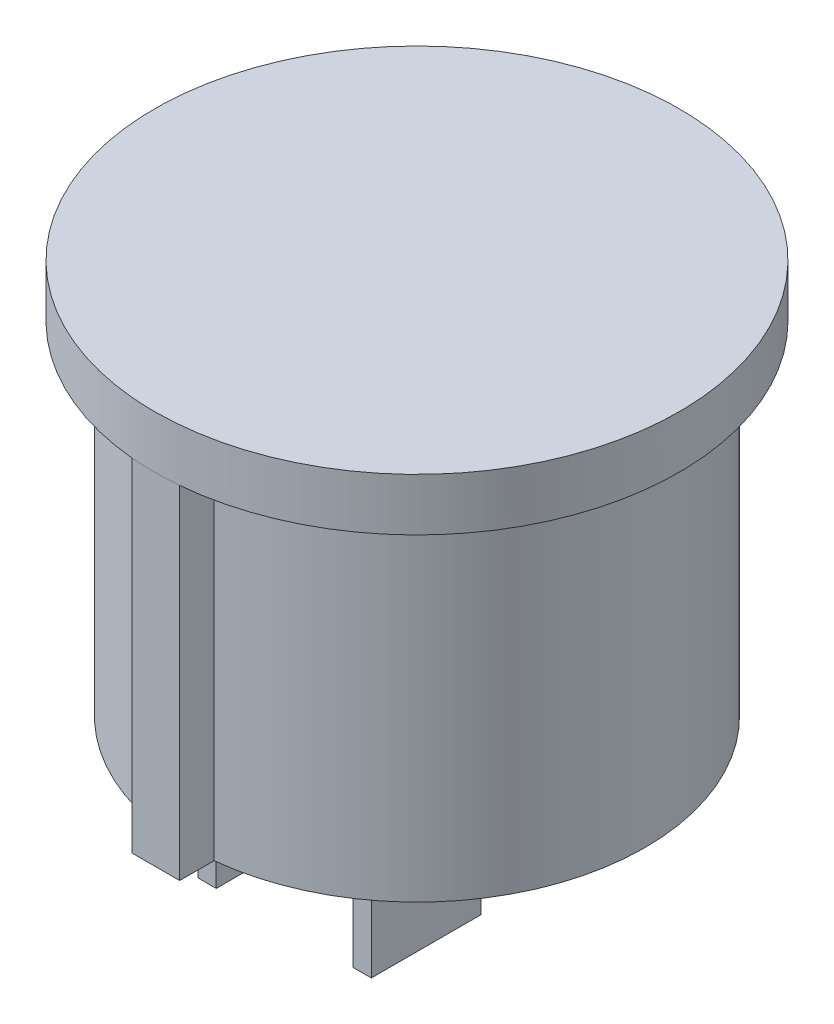
SolidWorks part; units mm, degrees
ref_plane "Front Plane" through (0, 0, 0) normal (0, 0, 1) x (1, 0, 0)
ref_plane "Top Plane" through (0, 0, 0) normal (0, 1, 0) x (1, 0, 0)
ref_plane "Right Plane" through (0, 0, 0) normal (1, 0, 0) x (0, 0, -1)
sketch "Sketch2" plane through (0, 0, 0) normal (0, 1, 0) x (1, 0, 0)
  circle A0 centre (0, 0) radius 10
  dimension "D1" = 20
extrude "Boss-Extrude1" add sketch "Sketch2" along normal blind 15
sketch "Sketch3" plane through (0, 15, 0) normal (0, 1, 0) x (1, 0, 0)
  circle A0 centre (0, 0) radius 11.5
  dimension "D1" = 23
extrude "Boss-Extrude2" add sketch "Sketch3" along normal blind 2.3
sketch "Sketch4" plane through (0, 0, 0) normal (0, -1, 0) x (1, 0, 0)
  line L1 (-0.4, -2.4) -> (0.4, -2.4)
  line L2 (-0.4, -2.4) -> (-0.4, 2.4)
  line L3 (-0.4, 2.4) -> (0.4, 2.4)
  line L4 (0.4, -2.4) -> (0.4, 2.4)
  line L5 (-0.4, -2.4) -> (0.4, 2.4) construction
  line L6 (-0.4, 2.4) -> (0.4, -2.4) construction
  line L11 (-7.2, -2.4) -> (-6.4, -2.4)
  line L12 (-7.2, -2.4) -> (-7.2, 2.4)
  line L13 (-7.2, 2.4) -> (-6.4, 2.4)
  line L14 (-6.4, -2.4) -> (-6.4, 2.4)
  line L15 (-7.2, -2.4) -> (-6.4, 2.4) construction
  line L16 (-7.2, 2.4) -> (-6.4, -2.4) construction
  point P0 (0, 0)
  point P5 (-6.8, 0)
  point P11 (-7.0164, 0)
  dimension "D1" = 4.8
  dimension "D2" = 0.8
  dimension "D3" = 6
extrude "Boss-Extrude3" add sketch "Sketch4" along normal blind 8.55
sketch "Sketch5" plane through (0, 0, 0) normal (0, -1, 0) x (1, 0, 0)
  line L2 (-1.05, 9.9447) -> (-1.05, 11.452)
  line L3 (-1.05, 11.452) -> (1.05, 11.452)
  line L4 (1.05, 9.9447) -> (1.05, 11.452)
  circle A0 centre (0, 0) radius 10 construction
  arc A1 (1.05, 9.9447) -> (-1.05, 9.9447) centre (0, 0) ccw
  circle A2 centre (0, 0) radius 10 construction
  circle A3 centre (0, 0) radius 11.5 construction
  point P6 (1.05, 11.452)
  point P7 (1.3257, 9.9117)
  point P10 (-1.2826, 9.9174)
  point P11 (0, 11.452)
  dimension "D1" = 2.1
extrude "Boss-Extrude4" add sketch "Sketch5" against normal up to surface (15 mm away) up to face at (0, 15, 10)
